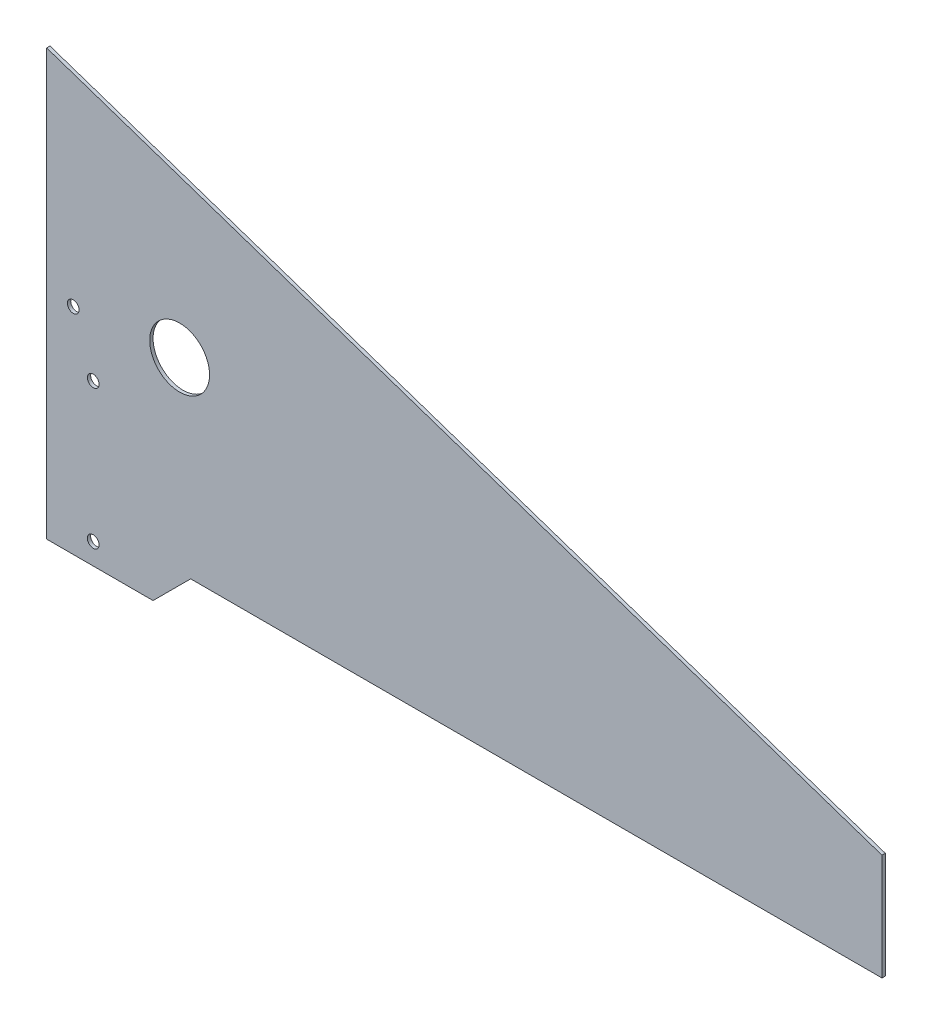
SolidWorks part; units mm, degrees
ref_plane "Front Plane" through (0, 0, 0) normal (0, 0, 1) x (1, 0, 0)
ref_plane "Top Plane" through (0, 0, 0) normal (0, 1, 0) x (1, 0, 0)
ref_plane "Right Plane" through (0, 0, 0) normal (1, 0, 0) x (0, 0, -1)
sketch "Sketch1" plane through (0, 0, 0) normal (0, 0, 1) x (1, 0, 0)
  line L0 (0, 0) -> (0, 203.2)
  line L1 (0, 203.2) -> (398.9605, 68.7605)
  line L2 (398.9605, 68.7605) -> (398.9605, 17.9605)
  line L3 (398.9605, 17.9605) -> (68.7605, 17.9605)
  line L4 (68.7605, 17.9605) -> (50.8, 0)
  line L5 (50.8, 0) -> (0, 0)
  dimension "D1" = 50.8
  dimension "D2" = 25.4
  dimension "D3" = 50.8
  dimension "D4" = 203.2
  dimension "D5" = 330.2
  dimension "D6" = 135
  dimension "D7" = 135
extrude "Boss-Extrude1" add sketch "Sketch1" along normal blind 1.5875
sketch "Sketch2" plane through (0, 0, 1.5875) normal (0, 0, 1) x (1, 0, 0)
  circle A0 centre (12.7, 102.5425) radius 2.54
  circle A1 centre (22.225, 10.1475) radius 2.54
  circle A2 centre (22.225, 76.5736) radius 2.54
  dimension "D1" = 5.08
hole_wizard "#10 Clearance Hole1" positions "Sketch4" profile "Sketch3" hole size "#10" standard "ANSI Inch" end condition through all
sketch "Sketch4" plane through (0, 0, 0) normal (0, 0, -1) x (-1, 0, 0)
  point P0 (-12.7, 102.5425)
  point P2 (-22.225, 76.5736)
  point P5 (-22.225, 10.1475)
sketch "Sketch3" plane through (12.7, 102.5425, 0) normal (1, 0, 0) x (0, 1, 0)
  line L0 (0, 0) -> (0, 1.5875)
  line L1 (0, 1.5875) -> (2.8067, 1.5875)
  line L2 (2.8067, 1.5875) -> (2.8067, 0)
  line L5 (2.8067, 0) -> (0, 0)
  line L11 (0, -6.35) -> (0, 107.95) construction
  dimension "Thru Hole Dia." = 5.6134
  dimension "Thru Hole Depth" = 1.5875
sketch "Sketch5" plane through (0, 0, 1.5875) normal (0, 0, 1) x (1, 0, 0)
  line L0 (0, 203.2) -> (0, 0) construction
  line L6 (68.7605, 17.9605) -> (398.9605, 17.9605) construction
  circle A0 centre (63.5, 106.8605) radius 31.75 construction
  circle A1 centre (63.5, 106.8605) radius 14.2875
  dimension "D1" = 63.5
  dimension "D4" = 28.575
  dimension "D2" = 63.5
  dimension "D3" = 88.9
extrude "Cut-Extrude1" cut sketch "Sketch5" against normal through all contours A1
